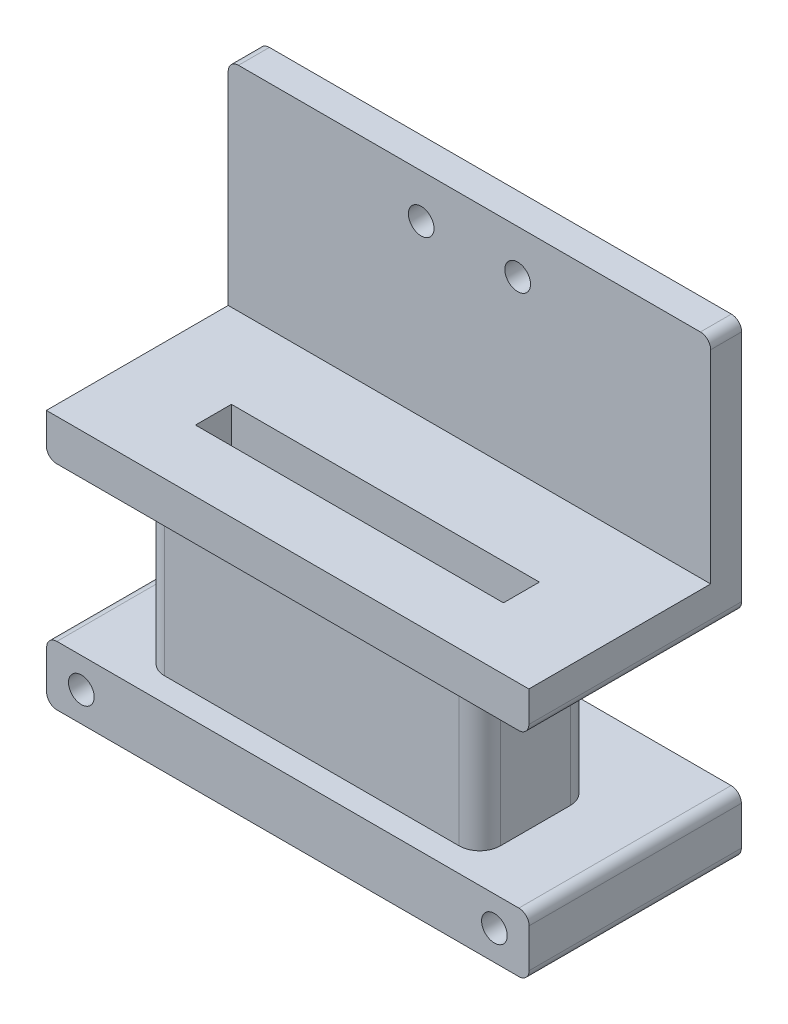
SolidWorks part; units mm, degrees
material "ABS PC"
ref_plane "Front Plane" through (0, 0, 0) normal (0, 0, 1) x (1, 0, 0)
ref_plane "Top Plane" through (0, 0, 0) normal (0, 1, 0) x (1, 0, 0)
ref_plane "Right Plane" through (0, 0, 0) normal (1, 0, 0) x (0, 0, -1)
sketch "Sketch1" plane through (0, 0, 0) normal (0, 1, 0) x (1, 0, 0)
  line L1 (-15, -1.75) -> (15, -1.75)
  line L2 (-15, -1.75) -> (-15, 1.75)
  line L3 (-15, 1.75) -> (15, 1.75)
  line L4 (15, -1.75) -> (15, 1.75)
  line L5 (-15, -1.75) -> (15, 1.75) construction
  line L6 (-15, 1.75) -> (15, -1.75) construction
  line L7 (-16.3541, 5.4119) -> (16.3541, 5.4119)
  line L8 (-16.3541, 5.4119) -> (-16.3541, -5.4119)
  line L9 (-16.3541, -5.4119) -> (16.3541, -5.4119)
  line L10 (16.3541, 5.4119) -> (16.3541, -5.4119)
  line L11 (-16.3541, 5.4119) -> (16.3541, -5.4119) construction
  line L12 (-16.3541, -5.4119) -> (16.3541, 5.4119) construction
  point P0 (0, 0)
  point P6 (0, 0)
  point P7 (0, 0)
extrude "Boss-Extrude2" add sketch "Sketch1" along normal blind 15
sketch "Sketch4" plane through (0, 15, 0) normal (0, 1, 0) x (1, 0, 0)
  line L1 (23.5, 7.7764) -> (-23.5, 7.7764)
  line L2 (23.5, 7.7764) -> (23.5, -7.7764)
  line L3 (23.5, -7.7764) -> (-23.5, -7.7764)
  line L4 (-23.5, 7.7764) -> (-23.5, -7.7764)
  line L5 (23.5, 7.7764) -> (-23.5, -7.7764) construction
  line L6 (23.5, -7.7764) -> (-23.5, 7.7764) construction
  line L7 (15, 1.75) -> (-15, 1.75)
  line L8 (15, 1.75) -> (15, -1.75)
  line L9 (15, -1.75) -> (-15, -1.75)
  line L10 (-15, 1.75) -> (-15, -1.75)
  line L11 (15, 1.75) -> (-15, -1.75) construction
  line L12 (15, -1.75) -> (-15, 1.75) construction
  point P0 (0, 0)
  point P6 (0, 0)
extrude "Boss-Extrude4" add sketch "Sketch4" along normal blind 4
sketch "Sketch7" plane through (0, 0, 0) normal (0, -1, 0) x (1, 0, 0)
  line L1 (-15, -1.75) -> (15, -1.75)
  line L2 (-15, -1.75) -> (-15, 1.75)
  line L3 (-15, 1.75) -> (15, 1.75)
  line L4 (15, -1.75) -> (15, 1.75)
  line L5 (-15, -1.75) -> (15, 1.75) construction
  line L6 (-15, 1.75) -> (15, -1.75) construction
  line L7 (-23.5, -7.75) -> (23.5, -7.75)
  line L8 (-23.5, -7.75) -> (-23.5, 7.75)
  line L9 (-23.5, 7.75) -> (23.5, 7.75)
  line L10 (23.5, -7.75) -> (23.5, 7.75)
  line L11 (-23.5, -7.75) -> (23.5, 7.75) construction
  line L12 (-23.5, 7.75) -> (23.5, -7.75) construction
  point P1 (0, 0)
  point P7 (0, 0)
extrude "Boss-Extrude5" add sketch "Sketch7" along normal blind 5.782
sketch "Sketch8" plane through (0, 0, -7.75) normal (0, 0, -1) x (-1, 0, 0)
  point P6 (-20.12, -2)
  point P7 (20.12, -2)
sketch "Sketch25" plane through (0, 0, -7.75) normal (0, 0, -1) x (-1, 0, 0)
  line L1 (-23.5, 0) -> (23.5, 0)
  line L2 (-23.5, 0) -> (-23.5, -5.782)
  line L3 (-23.5, -5.782) -> (23.5, -5.782)
  line L4 (23.5, 0) -> (23.5, -5.782)
  point P4 (0, 0)
  point P7 (0, 0)
  point P9 (0, 0)
extrude "Boss-Extrude9" add sketch "Sketch25" along normal blind 5.175
hole_wizard "M3x0.5 Tapped Hole1" positions "Sketch10" profile "Sketch9" tap size "M3x0.5" standard "ANSI Metric" end condition through all
sketch "Sketch10" plane through (0, 0, 7.75) normal (0, 0, -1) x (-1, 0, 0)
  line L1 (-977.5, -2.8912) -> (49022.5, -2.8912) construction
  point P0 (20.12, -2.8912)
  point P1 (-20.12, -2.8912)
sketch "Sketch9" plane through (-20.12, -2.8912, 7.75) normal (1, 0, 0) x (0, -1, 0)
  line L0 (0, 0) -> (0, 20.675)
  line L1 (0, 20.675) -> (1.25, 20.675)
  line L2 (1.25, 20.675) -> (1.25, 0)
  line L5 (1.25, 0) -> (0, 0)
  line L11 (0, -6.35) -> (0, 107.95) construction
  dimension "Thru Tap Drill Dia." = 2.5
  dimension "Thru Tap Drill Depth" = 20.675
sketch "Sketch13" plane through (23.5, 0, 0) normal (1, 0, 0) x (0, 0, -1)
  line L0 (0, 35.76) -> (0, 15) construction
  line L3 (-4, 25.38) -> (0, 25.38)
  line L4 (-4, 25.38) -> (-4, 35.76)
  line L6 (0, 25.38) -> (0, 35.76)
  line L8 (-4, 35.76) -> (0, 35.76)
  point P11 (0, 25.38)
fillet "Fillet5" radius 2 4 edges at (16.3541, 7.5, 5.4119) (-16.3541, 7.5, 5.4119) (-16.3541, 7.5, -5.4119) (16.3541, 7.5, -5.4119)
ref_plane "Plane2" through (23.5, 19, 7.7764) normal (1, 0, 0) x (0, 0, -1)
sketch "Sketch26" plane through (0, 0, -7.7764) normal (0, 0, -1) x (-1, 0, 0)
  line L5 (-23.5, 19) -> (23.5, 19)
  line L6 (-23.5, 19) -> (-23.5, 15)
  line L7 (-23.5, 15) -> (23.5, 15)
  line L8 (23.5, 19) -> (23.5, 15)
  point P4 (0, 0)
  point P6 (0, 0)
extrude "Boss-Extrude10" add sketch "Sketch26" along normal blind 5.175
sketch "Sketch17" plane through (0, 19, 0) normal (0, 1, 0) x (1, 0, 0)
  line L1 (-23.5, 12.9514) -> (23.5, 12.9514)
  line L2 (-23.5, 12.9514) -> (-23.5, 9.9361)
  line L3 (-23.5, 9.9361) -> (23.5, 9.9361)
  line L4 (23.5, 12.9514) -> (23.5, 9.9361)
  line L6 (-23.4969, 1.8116) -> (23.4538, 1.8116)
  line L8 (-23.5, 12.9514) -> (23.5, 12.9514) construction
  line L10 (-23.5, 12.9514) -> (-23.5, -7.7764) construction
  line L12 (23.5, -7.7764) -> (23.5, 12.9514) construction
  point P4 (-23.0603, 7.7097)
  point P5 (0, 0)
extrude "Boss-Extrude7" add sketch "Sketch17" along normal blind 20.76 contours L3 L4 L1 L2
hole_wizard "M3x0.5 Tapped Hole2" positions "Sketch21" profile "Sketch22" tap size "M3x0.5" standard "ANSI Metric" end condition through all
sketch "Sketch21" plane through (0, 0, -12.9514) normal (0, 0, -1) x (-1, 0, 0)
  line L0 (-4.7, 39.76) -> (-4.7, 35.51)
  line L3 (-23.5, 39.76) -> (-23.5, 15) construction
  line L4 (23.5, 39.76) -> (-23.5, 39.76) construction
  line L6 (-4.7, 35.51) -> (4.7, 35.51)
  point P0 (-4.7, 35.51)
  point P2 (4.7, 35.51)
  dimension "D1" = 18.8
  dimension "D2" = 9.4
  dimension "D3" = 4.25
sketch "Sketch22" plane through (4.7, 35.51, -12.9514) normal (1, 0, 0) x (0, 1, 0)
  line L0 (0, 0) -> (0, 20.7278)
  line L1 (0, 20.7278) -> (1.25, 20.7278)
  line L2 (1.25, 20.7278) -> (1.25, 0)
  line L5 (1.25, 0) -> (0, 0)
  line L11 (0, -6.35) -> (0, 107.95) construction
  dimension "Thru Tap Drill Dia." = 2.5
  dimension "Thru Tap Drill Depth" = 20.7278
sketch "Sketch24" plane through (0, 0, -7.75) normal (0, 0, -1) x (-1, 0, 0)
  line L0 (23.5, -5.782) -> (23.5, 0) construction
  line L1 (-23.5, 0) -> (23.5, 0)
  line L2 (-23.5, 0) -> (-23.5, -5.782)
  line L3 (-23.5, -5.782) -> (23.5, -5.782)
  line L4 (23.5, 0) -> (23.5, -5.782)
  line L5 (23.5, 0) -> (-23.5, 0) construction
  line L6 (23.5, -5.782) -> (23.5, 0) construction
  point P4 (0, 0)
  point P7 (0, 0)
  point P10 (0, 0)
fillet "Fillet6" radius 1 1 edges at (-23.5, 39.76, -11.4438)
fillet "Fillet8" radius 1 5 edges at (-23.5, 0, -2.5875) (-23.5, -5.782, -2.5875) (23.5, 0, -2.5875) (23.5, -5.782, -2.5875) (23.5, 39.76, -11.4438)
fillet "Fillet9" radius 1 1 edges at (-23.5, 15, -2.5875)
fillet "Fillet10" radius 1 1 edges at (23.5, 15, -2.5875)
